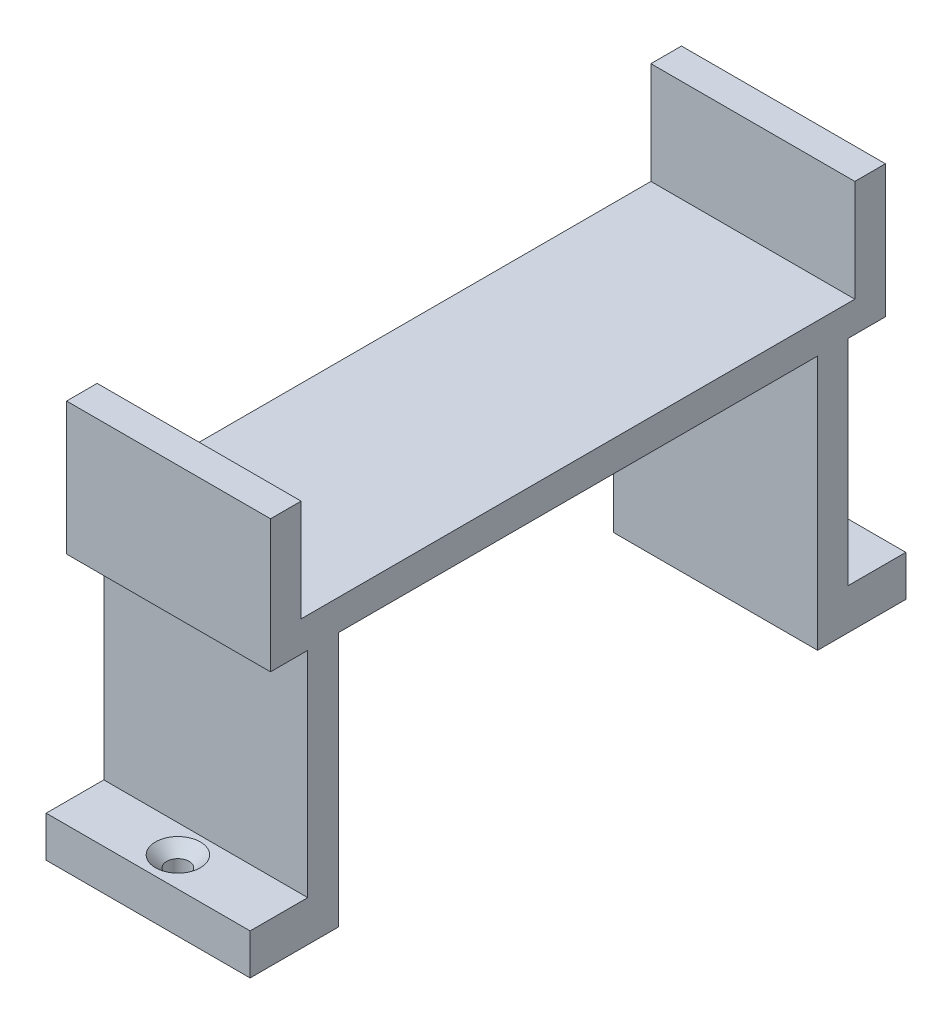
SolidWorks part; units mm, degrees
ref_plane "Front Plane" through (0, 0, 0) normal (0, 0, 1) x (1, 0, 0)
ref_plane "Top Plane" through (0, 0, 0) normal (0, 1, 0) x (1, 0, 0)
ref_plane "Right Plane" through (0, 0, 0) normal (1, 0, 0) x (0, 0, -1)
sketch "Sketch1" plane through (0, 0, 0) normal (1, 0, 0) x (0, 0, -1)
  line L1 (-30.15, 19) -> (30.15, 19)
  line L2 (-30.15, 19) -> (-30.15, -19)
  line L3 (-30.15, -19) -> (30.15, -19)
  line L4 (30.15, 19) -> (30.15, -19)
  line L5 (-30.15, 19) -> (30.15, -19) construction
  line L6 (-30.15, -19) -> (30.15, 19) construction
  point P0 (0, 0)
  dimension "D1" = 60.3
  dimension "D2" = 38
extrude "Boss-Extrude1" add sketch "Sketch1" along normal blind 10 contours L3 L4 L1 L2
sketch "Sketch3" plane through (0, 19, 0) normal (0, 1, 0) x (1, 0, 0)
  line L0 (10, -30.15) -> (10, 30.15) construction
  line L1 (-10, 27.15) -> (10, 27.15)
  line L2 (-10, 27.15) -> (-10, -27.15)
  line L3 (-10, -27.15) -> (10, -27.15)
  line L4 (10, 27.15) -> (10, -27.15)
  line L5 (-10, 27.15) -> (10, -27.15) construction
  line L6 (-10, -27.15) -> (10, 27.15) construction
  point P0 (0, 0)
  dimension "D1" = 54.3
extrude "Cut-Extrude1" cut sketch "Sketch3" against normal blind 10
sketch "Sketch4" plane through (0, -19, 0) normal (0, -1, 0) x (1, 0, 0)
  line L0 (10, 30.15) -> (10, -30.15) construction
  line L1 (-10, -23.5) -> (10, -23.5)
  line L2 (-10, -23.5) -> (-10, 23.5)
  line L3 (-10, 23.5) -> (10, 23.5)
  line L4 (10, -23.5) -> (10, 23.5)
  line L5 (-10, -23.5) -> (10, 23.5) construction
  line L6 (-10, 23.5) -> (10, -23.5) construction
  point P0 (0, 0)
  dimension "D1" = 47
extrude "Cut-Extrude2" cut sketch "Sketch4" against normal blind 25
sketch "Sketch6" plane through (0, 0, -30.15) normal (0, 0, -1) x (-1, 0, 0)
  line L0 (-10, 19) -> (-10, -19) construction
  line L1 (-10, 6) -> (0, 6)
  line L2 (-10, 6) -> (-10, -15)
  line L3 (-10, -15) -> (0, -15)
  line L4 (0, 6) -> (0, -15)
  line L5 (0, 19) -> (0, -19) construction
  line L6 (-10, -19) -> (0, -19) construction
  line L7 (-10, 19) -> (0, 19) construction
  point P8 (0, -4.5)
  dimension "D1" = 10
  dimension "D2" = 4
  dimension "D3" = 13
extrude "Cut-Extrude3" cut sketch "Sketch6" against normal blind 3.65
sketch "Sketch7" plane through (0, 0, 30.15) normal (0, 0, 1) x (1, 0, 0)
  line L0 (0, 19) -> (0, -19) construction
  line L1 (0, 6) -> (10, 6)
  line L2 (0, 6) -> (0, -15)
  line L3 (0, -15) -> (10, -15)
  line L4 (10, 6) -> (10, -15)
  line L5 (10, 19) -> (10, -19) construction
  line L6 (0, 19) -> (10, 19) construction
  line L7 (10, -19) -> (0, -19) construction
  dimension "D1" = 13
  dimension "D2" = 4
extrude "Cut-Extrude4" cut sketch "Sketch7" against normal blind 3.65
other "Move Face1" face at (5, -17, 30.15) face at (5, -17, -30.15) parameters "D1"=2
other "Move Face2" face at (0, -0.3, 0) parameters "D1"=10
sketch "Sketch13" plane through (0, -15, 0) normal (0, 1, 0) x (1, 0, 0)
  point P0 (0, -29.2327)
  point P2 (0, 29.4543)
hole_wizard "CSK for M2 Countersunk Flat Head Screw2" positions "Sketch13" profile "Sketch12" countersink size "M2" standard "ISO"
sketch "Sketch12" plane through (0, -15, 29.2327) normal (1, 0, 0) x (0, 0, 1)
  line L0 (0, 0) -> (0, 4)
  line L1 (0, 4) -> (1.1, 4)
  line L2 (1.1, 4) -> (1.1, 1.1)
  line L3 (1.1, 1.1) -> (2.2, 0)
  line L5 (2.2, 0) -> (0, 0)
  line L6 (-1.1, 1.1) -> (-2.2, 0) construction
  line L11 (0, -6.35) -> (0, 107.95) construction
  dimension "Thru Hole Dia." = 2.2
  dimension "Thru Hole Depth" = 4
  dimension "Near C'Sink Dia." = 4.4
  dimension "Near C'Sink Angle" = 90
